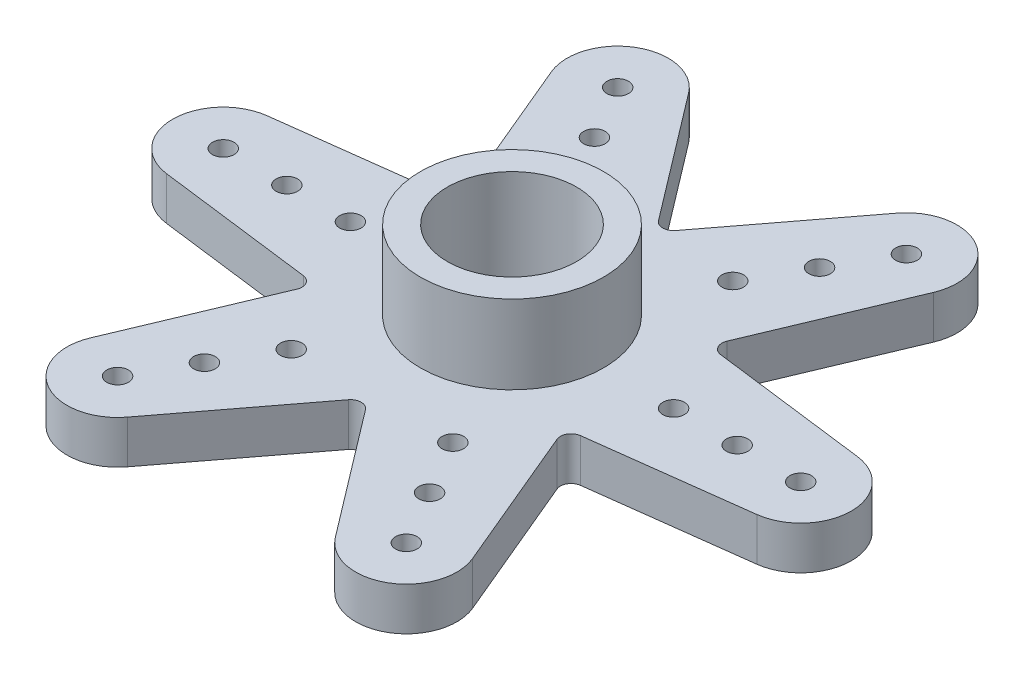
SolidWorks part; units mm, degrees
ref_plane "Front" through (0, 0, 0) normal (0, 0, 1) x (1, 0, 0)
ref_plane "Top" through (0, 0, 0) normal (0, 1, 0) x (1, 0, 0)
ref_plane "Right" through (0, 0, 0) normal (1, 0, 0) x (0, 0, -1)
sketch "Sketch1" plane through (0, 0, 0) normal (0, 1, 0) x (1, 0, 0)
  line L0 (-18.5403, 0) -> (17.9879, 0) construction
  line L1 (0, 0) -> (9.7356, 5.6209) construction
  line L2 (13.6961, 2.3313) -> (6.4322, 3.254)
  line L3 (13.6961, -2.3313) -> (6.4322, -3.254)
  line L4 (4.8291, -13.0268) -> (0.3981, -7.1974)
  line L5 (8.867, -10.6956) -> (6.0341, -3.9434)
  line L6 (-8.867, -10.6956) -> (-6.0341, -3.9434)
  line L7 (-4.8291, -13.0268) -> (-0.3981, -7.1974)
  line L8 (-13.6961, 2.3313) -> (-6.4322, 3.254)
  line L9 (-13.6961, -2.3313) -> (-6.4322, -3.254)
  line L10 (-4.8291, 13.0268) -> (-0.3981, 7.1974)
  line L11 (-8.867, 10.6956) -> (-6.0341, 3.9434)
  line L12 (8.867, 10.6956) -> (6.0341, 3.9434)
  line L13 (4.8291, 13.0268) -> (0.3981, 7.1974)
  circle A0 centre (0, 0) radius 15.75 construction
  circle A1 centre (0, 0) radius 3
  circle A2 centre (7.5, 0) radius 0.5
  circle A3 centre (10.45, 0) radius 0.5
  circle A4 centre (13.4, 0) radius 0.5
  circle A5 centre (3.75, -6.4952) radius 0.5
  circle A6 centre (5.225, -9.05) radius 0.5
  circle A7 centre (6.7, -11.6047) radius 0.5
  circle A8 centre (-3.75, -6.4952) radius 0.5
  circle A9 centre (-5.225, -9.05) radius 0.5
  circle A10 centre (-6.7, -11.6047) radius 0.5
  circle A11 centre (-7.5, 0) radius 0.5
  circle A12 centre (-10.45, 0) radius 0.5
  circle A13 centre (-13.4, 0) radius 0.5
  circle A14 centre (-3.75, 6.4952) radius 0.5
  circle A15 centre (-5.225, 9.05) radius 0.5
  circle A16 centre (-6.7, 11.6047) radius 0.5
  circle A17 centre (3.75, 6.4952) radius 0.5
  circle A18 centre (5.225, 9.05) radius 0.5
  circle A19 centre (6.7, 11.6047) radius 0.5
  arc A20 (13.6961, -2.3313) -> (13.6961, 2.3313) centre (13.4, 0) ccw
  circle A21 centre (0, 0) radius 7.5 construction
  arc A23 (4.8291, -13.0268) -> (8.867, -10.6956) centre (6.7, -11.6047) ccw
  arc A26 (-8.867, -10.6956) -> (-4.8291, -13.0268) centre (-6.7, -11.6047) ccw
  arc A29 (6.4322, -3.254) -> (6.0341, -3.9434) centre (6.4952, -3.75) ccw
  arc A31 (-13.6961, 2.3313) -> (-13.6961, -2.3313) centre (-13.4, 0) ccw
  arc A32 (-6.0341, -3.9434) -> (-6.4322, -3.254) centre (-6.4952, -3.75) ccw
  arc A38 (-4.8291, 13.0268) -> (-8.867, 10.6956) centre (-6.7, 11.6047) ccw
  arc A39 (-6.4322, 3.254) -> (-6.0341, 3.9434) centre (-6.4952, 3.75) ccw
  arc A40 (6.0341, 3.9434) -> (6.4322, 3.254) centre (6.4952, 3.75) ccw
  arc A41 (8.867, 10.6956) -> (4.8291, 13.0268) centre (6.7, 11.6047) ccw
  arc A42 (-0.3981, 7.1974) -> (0.3981, 7.1974) centre (0, 7.5) ccw
  arc A44 (0.3981, -7.1974) -> (-0.3981, -7.1974) centre (0, -7.5) ccw
  arc A45 (-0.1125, -7.9872) -> (0.4997, -7.4833) centre (0, -7.5) ccw [skipped]
  arc A46 (-0.1125, -7.9872) -> (0.4997, -7.4833) centre (0, -7.5) ccw [skipped]
  arc A47 (6.8609, -4.091) -> (6.7306, -3.3089) centre (6.4952, -3.75) ccw [skipped]
  arc A48 (6.8609, -4.091) -> (6.7306, -3.3089) centre (6.4952, -3.75) ccw [skipped]
  arc A49 (6.0341, 3.9434) -> (6.4322, 3.254) centre (6.4952, 3.75) ccw [skipped]
  arc A50 (-0.3981, 7.1974) -> (0.3981, 7.1974) centre (0, 7.5) ccw [skipped]
  arc A51 (-6.4322, 3.254) -> (-6.0341, 3.9434) centre (-6.4952, 3.75) ccw [skipped]
  arc A52 (-6.0341, -3.9434) -> (-6.4322, -3.254) centre (-6.4952, -3.75) ccw [skipped]
  dimension "D1" = 7.5
  dimension "D5" = 6
  dimension "D6" = 30
  dimension "D2" = 2.95
  dimension "D3" = 2.95
  dimension "D4" = 6
extrude "Boss-Extrude1" add sketch "Sketch1" along normal blind 2
sketch "Sketch2" plane through (0, 2, 0) normal (0, 1, 0) x (-1, 0, 0)
  circle A0 centre (0, 0) radius 4.25
  circle A1 centre (0, 0) radius 3
extrude "Boss-Extrude2" add sketch "Sketch2" along normal blind 3.65
